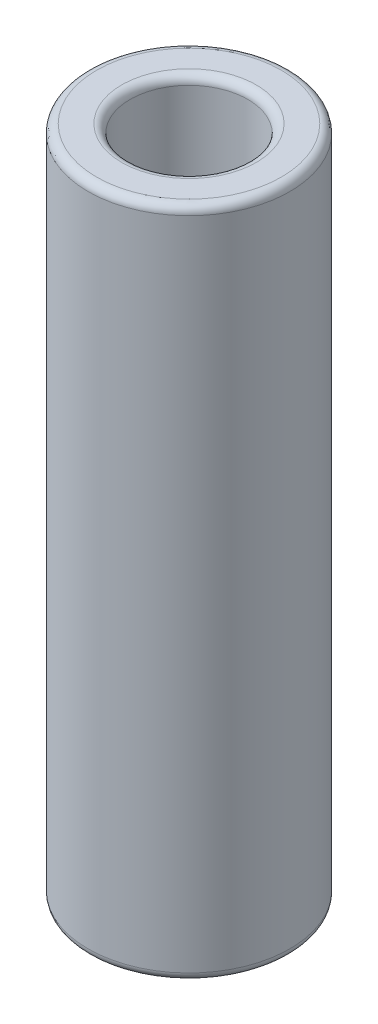
SolidWorks part; units mm, degrees
ref_plane "Płaszczyzna przednia" through (0, 0, 0) normal (0, 0, 1) x (1, 0, 0)
ref_plane "Płaszczyzna górna" through (0, 0, 0) normal (0, 1, 0) x (1, 0, 0)
ref_plane "Płaszczyzna prawa" through (0, 0, 0) normal (1, 0, 0) x (0, 0, -1)
sketch "Szkic1" plane through (0, 0, 0) normal (0, 1, 0) x (1, 0, 0)
  circle A0 centre (0, 0) radius 3.5
  circle A1 centre (0, 0) radius 6
  dimension "D1" = 7
  dimension "D2" = 12
extrude "Dodanie-wyciągnięcie2" add sketch "Szkic1" along normal blind 40
fillet "Zaokrąglenie1" radius 0.5 2 edges at (0, 40, 3.5) (0, 40, 6)
fillet "Zaokrąglenie2" radius 0.5 2 edges at (0, 0, 3.5) (0, 0, 6)
